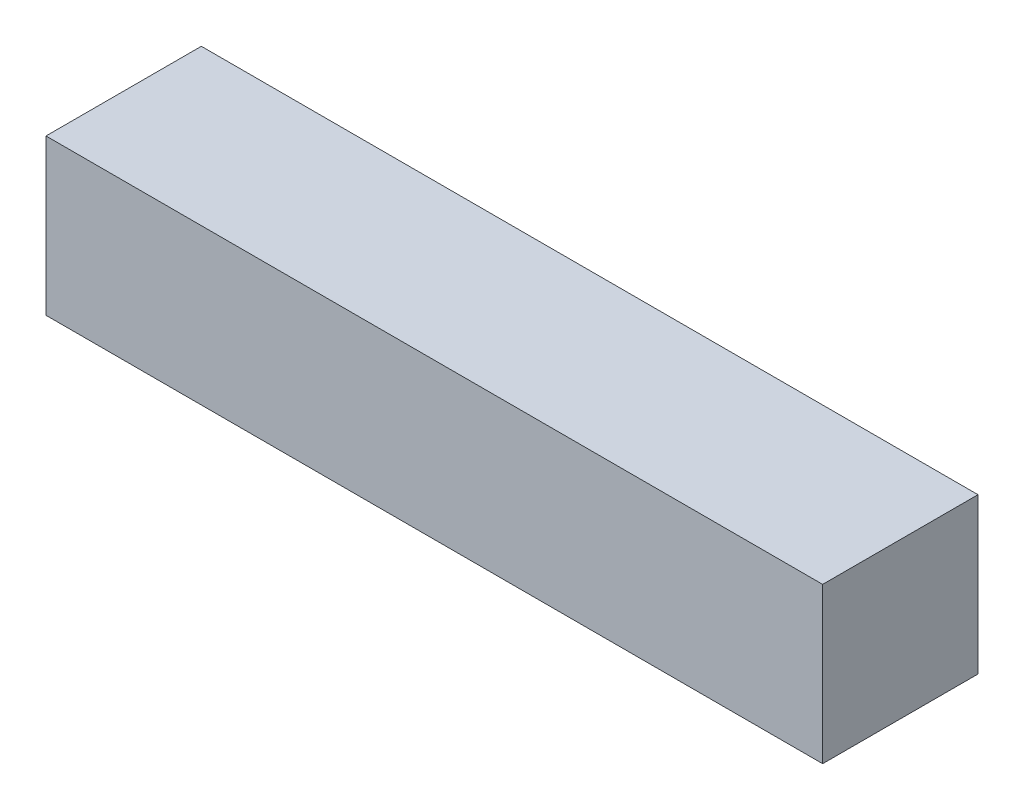
SolidWorks part; units mm, degrees
material "Plain Carbon Steel"
ref_plane "Front Plane" through (0, 0, 0) normal (0, 0, 1) x (1, 0, 0)
ref_plane "Top Plane" through (0, 0, 0) normal (0, 1, 0) x (1, 0, 0)
ref_plane "Right Plane" through (0, 0, 0) normal (1, 0, 0) x (0, 0, -1)
sketch "Sketch1" plane through (0, 0, 0) normal (1, 0, 0) x (0, 0, -1)
  line L1 (0, 0) -> (2, 0)
  line L2 (0, 0) -> (0, 2)
  line L3 (0, 2) -> (2, 2)
  line L4 (2, 0) -> (2, 2)
  dimension "D1" = 2
  dimension "D2" = 2
extrude "Boss-Extrude1" add sketch "Sketch1" along normal blind 10
